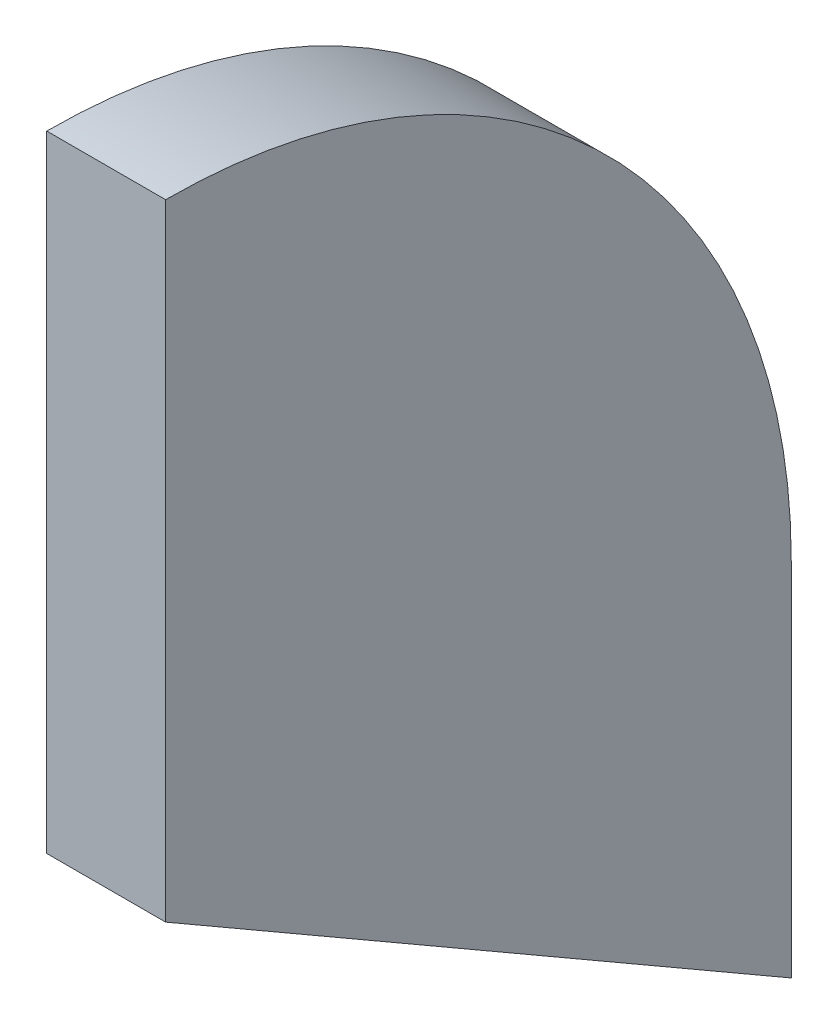
SolidWorks part; units mm, degrees
ref_plane "Front Plane" through (0, 0, 0) normal (0, 0, 1) x (1, 0, 0)
ref_plane "Top Plane" through (0, 0, 0) normal (0, 1, 0) x (1, 0, 0)
ref_plane "Right Plane" through (0, 0, 0) normal (1, 0, 0) x (0, 0, -1)
ref_plane "Plane1" through (270.5, 0, 0) normal (-1, 0, 0) x (0, -1, 0)
sketch "Sketch1" plane through (270.5, 0, 0) normal (-1, 0, 0) x (0, -1, 0)
  line L0 (0, -100) -> (57.735, -100)
  line L1 (57.735, -100) -> (0, 0)
  line L2 (0, 0) -> (-100, 0)
  arc A0 (-100, 0) -> (0, -100) centre (0, 0) ccw
extrude "Boss-Extrude1" add sketch "Sketch1" against normal blind 19
